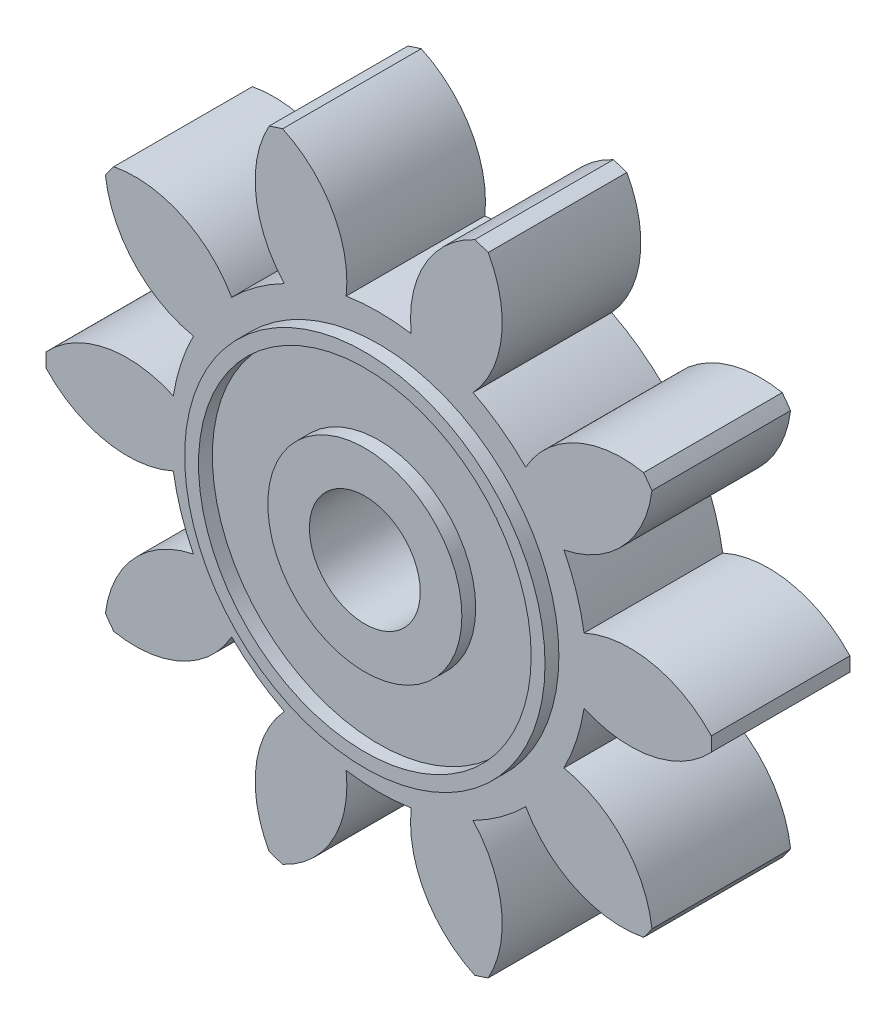
SolidWorks part; units mm, degrees
ref_plane "Front Plane" through (0, 0, 0) normal (0, 0, 1) x (1, 0, 0)
ref_plane "Top Plane" through (0, 0, 0) normal (0, 1, 0) x (1, 0, 0)
ref_plane "Right Plane" through (0, 0, 0) normal (1, 0, 0) x (0, 0, -1)
sketch "Sketch1" plane through (0, 0, 0) normal (0, 0, 1) x (1, 0, 0)
  circle A0 centre (0, 0) radius 12
  dimension "D1" = 24
extrude "Boss-Extrude1" add sketch "Sketch1" along normal mid plane 5
sketch "Sketch2" plane through (0, 0, 2.5) normal (0, 0, 1) x (1, 0, 0)
  line L0 (0, 0) -> (0, 12.025) construction
  circle A0 centre (0, 0) radius 7.5 construction
  circle A1 centre (0, 0) radius 12.025 construction
  arc A2 (1.1737, 7.4076) -> (-1.1737, 7.4076) centre (0, 0) ccw
  arc A3 (-3.4987, 11.5048) -> (3.4987, 11.5048) centre (0, 0) cw
  arc A4 (-1.1737, 7.4076) -> (-3.4987, 11.5048) centre (-5.1479, 7.8606) ccw
  arc A5 (1.1737, 7.4076) -> (3.4987, 11.5048) centre (5.1479, 7.8606) cw
  dimension "D1" = 24.05
  dimension "D2" = 15
  dimension "D5" = 4
  dimension "D3" = 2.357
  dimension "D4" = 7.1
extrude "Cut-Extrude2" cut sketch "Sketch2" against normal through all
pattern_circular "CirPattern2" count 10 over 360 about axis through (0, 0, 0) along (0, 0, 1) of "Cut-Extrude2"
sketch "Sketch3" plane through (0, 0, 2.5) normal (0, 0, 1) x (1, 0, 0)
  circle A0 centre (0, 0) radius 2
  dimension "D1" = 4
extrude "Cut-Extrude3" cut sketch "Sketch3" against normal through all
sketch "Sketch4" plane through (0, 0, 2.5) normal (0, 0, 1) x (1, 0, 0)
  circle A0 centre (0, 0) radius 2 construction
  circle A1 centre (0, 0) radius 2
  circle A2 centre (0, 0) radius 6.5
  circle A3 centre (0, 0) radius 6
  circle A4 centre (0, 0) radius 3.5
  circle M2 centre (0, 0) radius 2
  dimension "D1" = 13
  dimension "D2" = 12
  dimension "D3" = 7
extrude "Boss-Extrude2" add sketch "Sketch4" along normal blind 0.5 contours A4 M2 | A2 A3
mirror "Mirror1" about plane through (0, 0, 0) normal (0, 0, 1) of "Boss-Extrude2"
